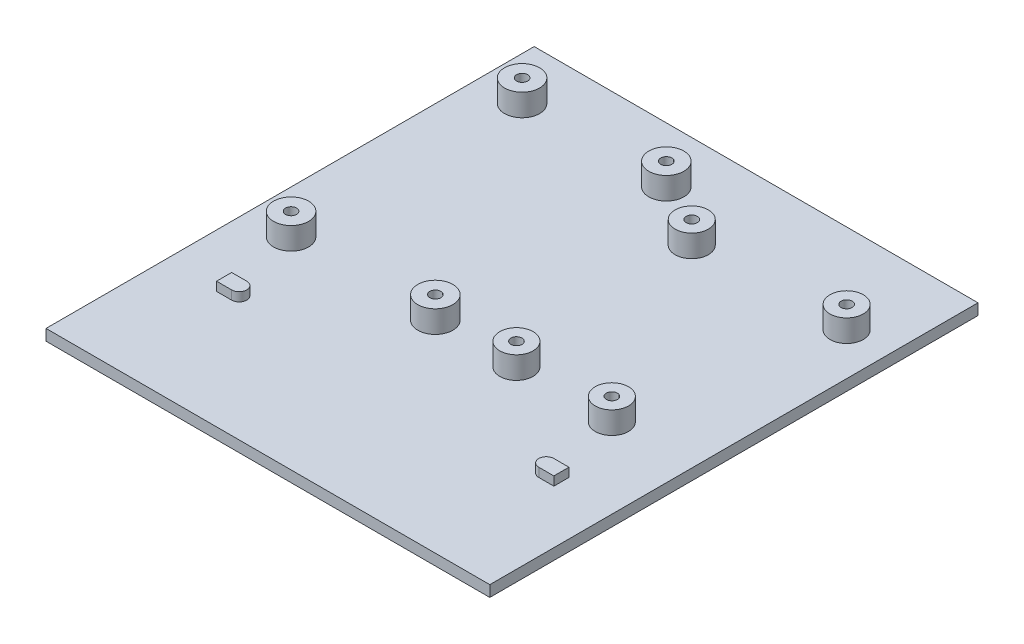
SolidWorks part; units mm, degrees
ref_plane "Front Plane" through (0, 0, 0) normal (0, 0, 1) x (1, 0, 0)
ref_plane "Top Plane" through (0, 0, 0) normal (0, 1, 0) x (1, 0, 0)
ref_plane "Right Plane" through (0, 0, 0) normal (1, 0, 0) x (0, 0, -1)
sketch "Sketch1" plane through (0, 0, 0) normal (0, 1, 0) x (1, 0, 0)
  line L0 (9.525, -85.09) -> (149.5329, -85.09) construction
  line L1 (0, 0) -> (127, 0) construction
  line L2 (0, 0) -> (0, -139.7) construction
  line L3 (0, -139.7) -> (127, -139.7) construction
  line L4 (127, 0) -> (127, -139.7) construction
  line L6 (15.24, -101.8159) -> (15.24, -106.1339)
  line L8 (111.76, -101.8159) -> (111.76, -106.1339)
  line L9 (9.525, -12.7) -> (56.515, -12.7) construction
  line L10 (9.525, -12.7) -> (9.525, -85.09) construction
  line L11 (9.525, -85.09) -> (56.515, -85.09) construction
  line L12 (56.515, -12.7) -> (56.515, -85.09) construction
  line L13 (117.475, -85.09) -> (69.215, -85.09) construction
  line L14 (117.475, -85.09) -> (117.475, -11.43) construction
  line L15 (117.475, -11.43) -> (69.215, -11.43) construction
  line L16 (69.215, -85.09) -> (69.215, -11.43) construction
  line L17 (15.24, -106.1339) -> (19.558, -106.1339) construction
  line L18 (15.24, -101.8159) -> (19.558, -101.8159) construction
  line L19 (107.442, -101.8159) -> (111.76, -101.8159) construction
  line L20 (111.76, -101.8159) -> (107.442, -101.8159)
  line L21 (111.76, -101.8159) -> (111.76, -106.1339)
  line L22 (111.76, -106.1339) -> (107.442, -106.1339)
  line L24 (15.24, -101.8159) -> (19.558, -101.8159)
  line L25 (15.24, -101.8159) -> (15.24, -106.1339)
  line L26 (15.24, -106.1339) -> (19.558, -106.1339)
  line L28 (107.442, -106.1339) -> (111.76, -106.1339) construction
  line L29 (76.835, -81.915) -> (104.14, -81.915) construction
  line L30 (12.3825, -15.8433) -> (53.6575, -15.8433) construction
  line L31 (12.3825, -15.8433) -> (12.3825, -81.9468) construction
  line L32 (12.3825, -81.9468) -> (53.6575, -81.9468) construction
  line L33 (53.6575, -15.8433) -> (53.6575, -81.9468) construction
  line L35 (0, 0) -> (127, 0)
  line L36 (0, 0) -> (0, -139.7)
  line L37 (0, -139.7) -> (127, -139.7)
  line L38 (127, 0) -> (127, -139.7)
  arc A0 (19.558, -106.1339) -> (19.558, -101.8159) centre (19.558, -103.9749) ccw
  arc A1 (107.442, -101.8159) -> (107.442, -106.1339) centre (107.442, -103.9749) ccw
  circle A3 centre (12.3825, -15.8433) radius 5.0165
  circle A5 centre (53.6575, -15.8433) radius 5.0165
  circle A7 centre (12.3825, -81.9468) radius 5.0165
  circle A9 centre (53.6575, -81.9468) radius 5.0165
  circle A10 centre (71.755, -26.67) radius 1.5875
  circle A11 centre (71.755, -26.67) radius 4.7625
  circle A12 centre (76.835, -81.915) radius 1.5875
  circle A13 centre (76.835, -81.915) radius 4.7625
  circle A14 centre (104.14, -81.915) radius 1.5875
  circle A15 centre (104.14, -81.915) radius 4.7625
  circle A16 centre (114.935, -25.527) radius 1.5875
  circle A17 centre (114.935, -25.527) radius 4.7625
  circle A18 centre (53.6575, -15.8433) radius 1.5875
  circle A19 centre (12.3825, -15.8433) radius 1.5875
  circle A20 centre (12.3825, -81.9468) radius 1.5875
  circle A21 centre (53.6575, -81.9468) radius 1.5875
  dimension "D18" = 2.159
  dimension "D19" = 2.159
  dimension "D22" = 10.033
  dimension "D26" = 3.175
  dimension "D27" = 9.525
  dimension "D30" = 2.54
  dimension "D1" = 127
  dimension "D2" = 139.7
  dimension "D3" = 33.5661
  dimension "D4" = 15.24
  dimension "D5" = 15.24
  dimension "D6" = 41.275
  dimension "D7" = 46.99
  dimension "D8" = 72.39
  dimension "D9" = 9.525
  dimension "D10" = 66.1035
  dimension "D11" = 48.26
  dimension "D12" = 73.66
  dimension "D13" = 9.525
  dimension "D14" = 3.1433
  dimension "D15" = 4.318
  dimension "D16" = 4.318
  dimension "D17" = 4.318
  dimension "D20" = 2.8575
  dimension "D23" = 27.305
  dimension "D24" = 7.62
  dimension "D25" = 3.175
  dimension "D28" = 2.54
  dimension "D29" = 15.24
  dimension "D31" = 14.097
extrude "Boss-Extrude5" add sketch "Sketch1" along normal blind 3.175 contours L37 L38 L35 L36
sketch "Sketch2" plane through (0, 3.175, 0) normal (0, 1, 0) x (1, 0, 0)
  line L0 (15.24, -106.1339) -> (15.24, -101.8159)
  line L1 (15.24, -101.8159) -> (19.558, -101.8159)
  line L2 (15.24, -106.1339) -> (19.558, -106.1339)
  line L3 (107.442, -101.8159) -> (111.76, -101.8159)
  line L4 (111.76, -101.8159) -> (111.76, -106.1339)
  line L5 (111.76, -106.1339) -> (107.442, -106.1339)
  circle A0 centre (12.3825, -15.8433) radius 5.0165
  circle A1 centre (53.6575, -15.8433) radius 5.0165
  circle A2 centre (71.755, -26.67) radius 4.7625
  circle A3 centre (114.935, -25.527) radius 4.7625
  circle A4 centre (104.14, -81.915) radius 4.7625
  circle A5 centre (76.835, -81.915) radius 4.7625
  circle A6 centre (53.6575, -81.9468) radius 5.0165
  circle A7 centre (12.3825, -81.9468) radius 5.0165
  circle A8 centre (12.3825, -15.8433) radius 1.5875
  circle A9 centre (53.6575, -15.8433) radius 1.5875
  circle A10 centre (71.755, -26.67) radius 1.5875
  circle A11 centre (114.935, -25.527) radius 1.5875
  circle A12 centre (104.14, -81.915) radius 1.5875
  circle A13 centre (76.835, -81.915) radius 1.5875
  circle A14 centre (53.6575, -81.9468) radius 1.5875
  circle A15 centre (12.3825, -81.9468) radius 1.5875
  arc A16 (19.558, -106.1339) -> (19.558, -101.8159) centre (19.558, -103.9749) ccw
  arc A17 (107.442, -101.8159) -> (107.442, -106.1339) centre (107.442, -103.9749) ccw
extrude "Boss-Extrude6" add sketch "Sketch2" along normal blind 6.35
sketch "Sketch3" plane through (0, 9.525, 0) normal (0, 1, 0) x (1, 0, 0)
  line L0 (19.558, -101.8159) -> (15.24, -101.8159)
  line L1 (15.24, -101.8159) -> (15.24, -106.1339)
  line L2 (15.24, -106.1339) -> (19.558, -106.1339)
  line L3 (63.5, -139.7) -> (63.5, 0) construction
  line L4 (0, -139.7) -> (127, -139.7) construction
  line L5 (0, 0) -> (127, 0) construction
  line L6 (111.76, -106.1339) -> (107.442, -106.1339)
  line L7 (111.76, -101.8159) -> (111.76, -106.1339)
  line L8 (107.442, -101.8159) -> (111.76, -101.8159)
  arc A0 (19.558, -106.1339) -> (19.558, -101.8159) centre (19.558, -103.9749) ccw
  arc A1 (107.442, -106.1339) -> (107.442, -101.8159) centre (107.442, -103.9749) cw
extrude "Cut-Extrude2" cut sketch "Sketch3" against normal blind 3.81
